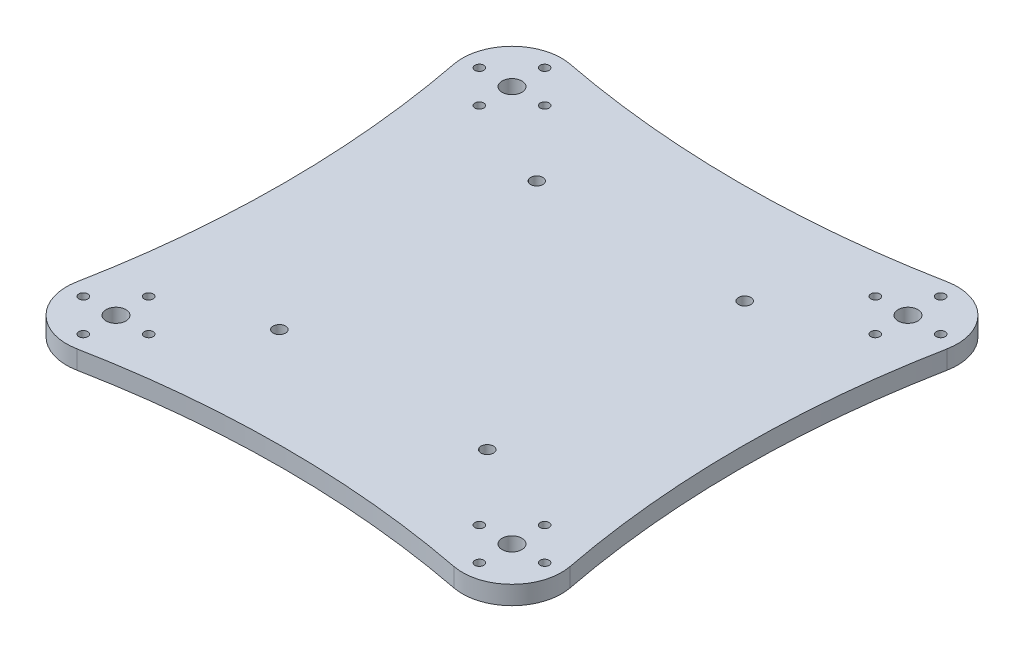
SolidWorks part; units mm, degrees
ref_plane "Front Plane" through (0, 0, 0) normal (0, 0, 1) x (1, 0, 0)
ref_plane "Top Plane" through (0, 0, 0) normal (0, 1, 0) x (1, 0, 0)
ref_plane "Right Plane" through (0, 0, 0) normal (1, 0, 0) x (0, 0, -1)
sketch "Sketch1" plane through (0, 0, 0) normal (0, 1, 0) x (1, 0, 0)
  line L4 (-50.8, 50.8) -> (50.8, -50.8) construction
  line L5 (26.67, 33.02) -> (-26.67, -33.02) construction
  arc A0 (-48.381, 63.2675) -> (-63.2675, 48.381) centre (-50.8, 50.8) ccw
  arc A1 (-63.2675, -48.381) -> (-48.381, -63.2675) centre (-50.8, -50.8) ccw
  arc A2 (48.381, -63.2675) -> (63.2675, -48.381) centre (50.8, -50.8) ccw
  arc A3 (63.2675, 48.381) -> (48.381, 63.2675) centre (50.8, 50.8) ccw
  circle A8 centre (-26.67, 33.02) radius 1.5875
  circle A9 centre (26.67, 33.02) radius 1.5875
  circle A10 centre (-26.67, -33.02) radius 1.5875
  circle A11 centre (26.67, -33.02) radius 1.5875
  arc A12 (-48.381, 63.2675) -> (48.381, 63.2675) centre (0, 312.6172) ccw
  arc A13 (-63.2675, 48.381) -> (-63.2675, -48.381) centre (-312.6172, 0) cw
  arc A14 (63.2675, 48.381) -> (63.2675, -48.381) centre (312.6172, 0) ccw
  arc A15 (48.381, -63.2675) -> (-48.381, -63.2675) centre (0, -312.6172) ccw
  point P16 (0, 0)
  point P26 (0, 0)
  dimension "D3" = 12.7
  dimension "D7" = 3.175
  dimension "D8" = 254
  dimension "D1" = 101.6
  dimension "D2" = 101.6
  dimension "D5" = 53.34
  dimension "D6" = 66.04
extrude "Boss-Extrude1" add sketch "Sketch1" along normal blind 4.7625
sketch "Sketch11" plane through (0, 4.7625, 0) normal (0, 1, 0) x (1, 0, 0)
  arc A0 (-48.381, 63.2675) -> (-63.2675, 48.381) centre (-50.8, 50.8) ccw construction
  arc A1 (-48.381, 63.2675) -> (-63.2675, 48.381) centre (-50.8, 50.8) ccw construction
  circle A2 centre (-50.8, 50.8) radius 2.54
  circle A3 centre (-42.418, 50.8) radius 1.143
  circle A4 centre (-50.8, 42.418) radius 1.143
  circle A5 centre (-59.182, 50.8) radius 1.143
  circle A6 centre (-50.8, 59.182) radius 1.143
  circle A7 centre (50.8, 50.8) radius 2.54
  circle A8 centre (59.182, 50.8) radius 1.143
  circle A9 centre (50.8, 42.418) radius 1.143
  circle A10 centre (42.418, 50.8) radius 1.143
  circle A11 centre (50.8, 59.182) radius 1.143
  circle A12 centre (50.8, -50.8) radius 2.54
  circle A13 centre (59.182, -50.8) radius 1.143
  circle A14 centre (50.8, -59.182) radius 1.143
  circle A15 centre (42.418, -50.8) radius 1.143
  circle A16 centre (50.8, -42.418) radius 1.143
  circle A17 centre (-50.8, -50.8) radius 2.54
  circle A18 centre (-42.418, -50.8) radius 1.143
  circle A19 centre (-50.8, -59.182) radius 1.143
  circle A20 centre (-59.182, -50.8) radius 1.143
  circle A21 centre (-50.8, -42.418) radius 1.143
  arc A22 (48.381, -63.2675) -> (63.2675, -48.381) centre (50.8, -50.8) ccw construction
  arc A23 (48.381, -63.2675) -> (63.2675, -48.381) centre (50.8, -50.8) ccw construction
  point P15 (-50.8, 50.8)
  point P26 (50.8, 50.8)
  point P37 (50.8, -50.8)
  point P48 (-50.8, -50.8)
  dimension "D1" = 5.08
  dimension "D2" = 2.286
  dimension "D3" = 8.382
  dimension "D5" = 2
  dimension "D6" = 2
  dimension "D4" = 4
extrude "Cut-Extrude1" cut sketch "Sketch11" against normal through all
